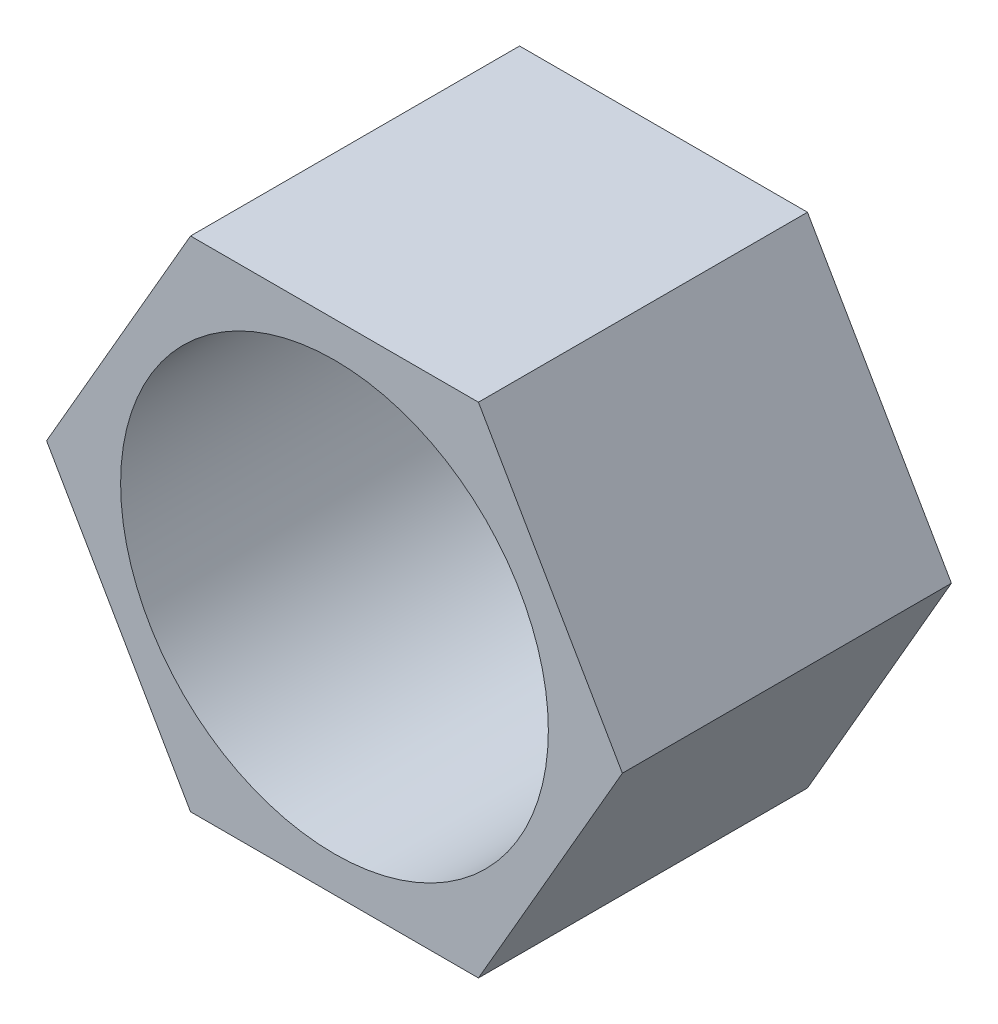
SolidWorks part; units mm, degrees
ref_plane "Front Plane" through (0, 0, 0) normal (0, 0, 1) x (1, 0, 0)
ref_plane "Top Plane" through (0, 0, 0) normal (0, 1, 0) x (1, 0, 0)
ref_plane "Right Plane" through (0, 0, 0) normal (1, 0, 0) x (0, 0, -1)
sketch "Sketch1" plane through (0, 0, 0) normal (0, 0, 1) x (1, 0, 0)
  line L1 (0.175, 0) -> (0.0875, 0.1516)
  line L2 (0.0875, 0.1516) -> (-0.0875, 0.1516)
  line L3 (-0.0875, 0.1516) -> (-0.175, 0)
  line L4 (-0.175, 0) -> (-0.0875, -0.1516)
  line L5 (-0.0875, -0.1516) -> (0.0875, -0.1516)
  line L6 (0.0875, -0.1516) -> (0.175, 0)
  circle A0 centre (0, 0) radius 0.1516 construction
  dimension "D1" = 0.35
extrude "Boss-Extrude1" add sketch "Sketch1" along normal mid plane 0.2
sketch "Sketch2" plane through (0, 0, 0.1) normal (0, 0, 1) x (1, 0, 0)
  circle A0 centre (0, 0) radius 0.13
  dimension "D1" = 0.26
extrude "Cut-Extrude1" cut sketch "Sketch2" against normal blind 0.2
